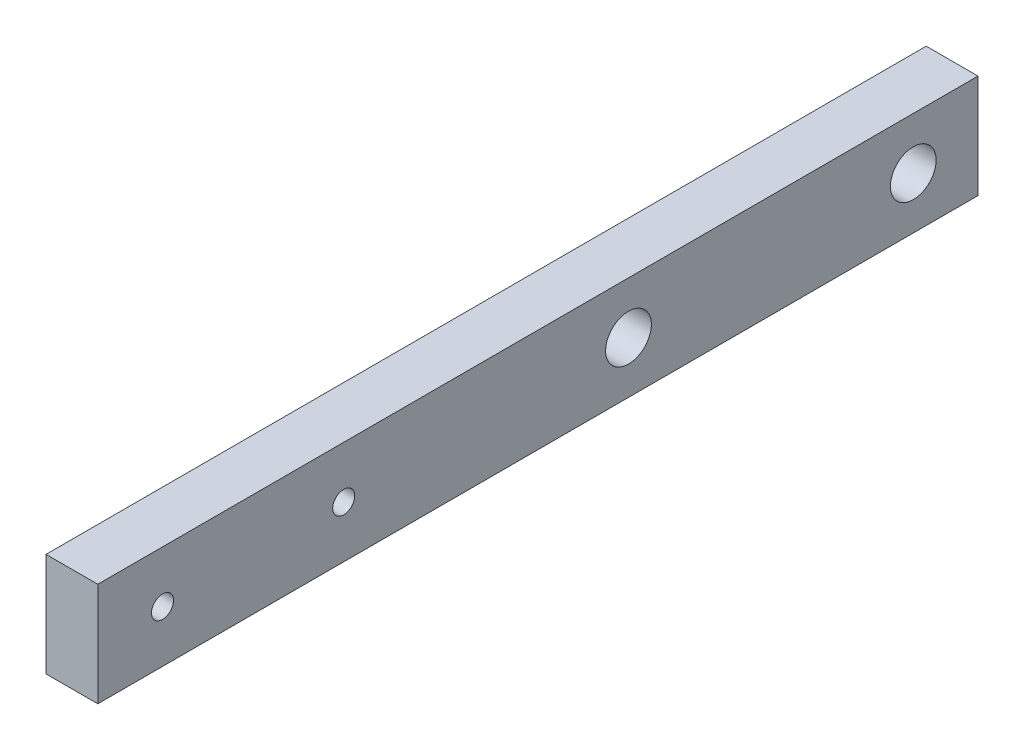
SolidWorks part; units mm, degrees
ref_plane "Front" through (0, 0, 0) normal (0, 0, 1) x (1, 0, 0)
ref_plane "Top" through (0, 0, 0) normal (0, 1, 0) x (1, 0, 0)
ref_plane "Right" through (0, 0, 0) normal (1, 0, 0) x (0, 0, -1)
sketch "Sketch1" plane through (0, 0, 0) normal (0, 0, 1) x (1, 0, 0)
  line L1 (0, 0) -> (6.35, 0)
  line L2 (0, 0) -> (0, 12.7)
  line L3 (0, 12.7) -> (6.35, 12.7)
  line L4 (6.35, 0) -> (6.35, 12.7)
  dimension "D1" = 6.35
  dimension "D2" = 12.7
extrude "Extrude1" add sketch "Sketch1" along normal blind 107.95
hole_wizard "#10 Clearance Hole1" positions "Sketch3" profile "Sketch4" hole size "#10" standard "Ansi Inch" end condition through all
sketch "Sketch3" plane through (6.35, 0, 0) normal (1, 0, 0) x (0, 0, -1)
  line L0 (-107.95, 0) -> (0, 0) construction
  line L1 (0, 0) -> (0, 12.7) construction
  point P0 (-42.8625, 6.35)
  point P1 (-7.9375, 6.35)
  dimension "D1" = 34.925
  dimension "D2" = 6.35
  dimension "D3" = 7.9375
sketch "Sketch4" plane through (6.35, 6.35, 42.8625) normal (0, 1, 0) x (0, 0, -1)
  line L0 (0, 0) -> (0, 6.35)
  line L1 (0, 6.35) -> (2.8067, 6.35)
  line L2 (2.8067, 6.35) -> (2.8067, 0)
  line L5 (2.8067, 0) -> (0, 0)
  line L11 (0, -6.35) -> (0, 107.95) construction
  dimension "Thru Hole Dia." = 5.6134
  dimension "Thru Hole Depth" = 6.35
hole_wizard "#6-32 Tapped Hole1" positions "Sketch8" profile "Sketch7" tap size "#6-32" standard "Ansi Inch" end condition through all
sketch "Sketch8" plane through (0, 0, 0) normal (-1, 0, 0) x (0, 0, 1)
  point P0 (100.0125, 6.35)
  point P1 (77.7875, 6.35)
  dimension "D1" = 22.225
  dimension "D2" = 34.925
sketch "Sketch7" plane through (0, 6.35, 100.0125) normal (0, 1, 0) x (0, 0, 1)
  line L0 (0, 0) -> (0, 6.35)
  line L1 (0, 6.35) -> (1.3525, 6.35)
  line L2 (1.3525, 6.35) -> (1.3525, 0)
  line L5 (1.3525, 0) -> (0, 0)
  line L11 (0, -6.35) -> (0, 107.95) construction
  dimension "Thru Tap Drill Dia." = 2.7051
  dimension "Thru Tap Drill Depth" = 6.35
cosmetic thread "Hole Thread1"
cosmetic thread "Hole Thread2"
